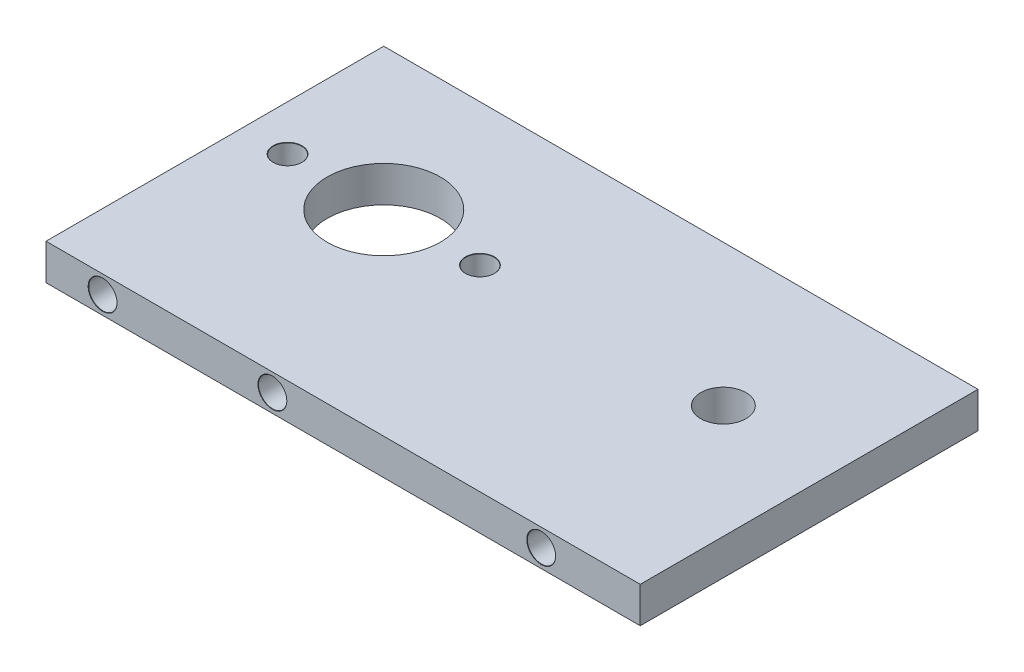
SolidWorks part; units mm, degrees
ref_plane "Front Plane" through (0, 0, 0) normal (0, 0, 1) x (1, 0, 0)
ref_plane "Top Plane" through (0, 0, 0) normal (0, 1, 0) x (1, 0, 0)
ref_plane "Right Plane" through (0, 0, 0) normal (1, 0, 0) x (0, 0, -1)
sketch "Sketch1" plane through (0, 0, 0) normal (0, 1, 0) x (1, 0, 0)
  line L0 (-12.5, -12.5) -> (-12.5, -17.34)
  line L1 (12.5, -12.5) -> (-12.5, -12.5) construction
  line L2 (12.5, -12.5) -> (12.5, 12.5)
  line L3 (12.5, 12.5) -> (-12.5, 12.5)
  line L4 (-12.5, -12.5) -> (-12.5, 12.5)
  line L5 (12.5, -12.5) -> (-12.5, 12.5) construction
  line L6 (12.5, 12.5) -> (-12.5, -12.5) construction
  line L7 (-12.5, -17.34) -> (12.5, -17.34)
  line L8 (12.5, -17.34) -> (12.5, -12.5)
  circle A0 centre (0, 0) radius 12.5 construction
  point P0 (0, 0)
  dimension "D1" = 25
  dimension "D2" = 17.34
extrude "Boss-Extrude1" add sketch "Sketch1" along normal blind 3.175
sketch "Sketch2" plane through (0, 3.175, 0) normal (0, 1, 0) x (1, 0, 0)
  line L0 (-8.5, 0) -> (8.5, 0) construction
  point P0 (-8.5, 0)
  point P1 (8.5, 0)
  point P2 (0, 0)
  dimension "D1" = 17
hole_wizard "Tap Drill for M3x0.5 Tap1" positions "Sketch2" profile "Sketch4" hole size "M3x0.5" standard "ANSI Metric" end condition through all
sketch "Sketch4" plane through (-8.5, 3.175, 0) normal (1, 0, 0) x (0, 0, 1)
  line L0 (0, 0) -> (0, 3.175)
  line L1 (0, 3.175) -> (1.25, 3.175)
  line L2 (1.25, 3.175) -> (1.25, 0.025)
  line L3 (1.25, 0.025) -> (1.275, 0)
  line L5 (1.275, 0) -> (0, 0)
  line L6 (-1.25, 0.025) -> (-1.275, 0) construction
  line L11 (0, -6.35) -> (0, 107.95) construction
  dimension "Thru Hole Dia." = 2.5
  dimension "Thru Hole Depth" = 3.175
  dimension "Near C'Sink Dia." = 2.55
  dimension "Near C'Sink Angle" = 90
sketch "Sketch8" plane through (0, 3.175, 0) normal (0, 1, 0) x (1, 0, 0)
  circle A0 centre (0, 0) radius 5
  dimension "D1" = 10
extrude "Cut-Extrude1" cut sketch "Sketch8" against normal up to next
sketch "Sketch9" plane through (0, 3.175, 0) normal (0, 1, 0) x (1, 0, 0)
  line L0 (0, 0) -> (30, 0) construction
  line L1 (12.5, 12.5) -> (40, 12.5)
  line L2 (40, 12.5) -> (40, -17.34)
  line L3 (40, -17.34) -> (12.5, -17.34)
  circle A0 centre (30, 0) radius 2
  dimension "D2" = 4
  dimension "D1" = 30
  dimension "D3" = 10
extrude "Boss-Extrude2" add sketch "Sketch9" against normal up to surface (3.175 mm away)
hole_wizard "Tap Drill for M3x0.5 Tap2" positions "Sketch7" profile "Sketch6" hole size "M3x0.5" standard "ANSI Metric"
sketch "Sketch7" plane through (0, 0, 17.34) normal (0, 0, 1) x (1, 0, 0)
  line L0 (-7.5, 1.5875) -> (7.5, 1.5875) construction
  line L2 (-12.5, 3.175) -> (40, 3.175) construction
  line L3 (-12.5, 0) -> (40, 0) construction
  line L4 (7.5, 1.5875) -> (40, 1.5875) construction
  line L5 (40, 0) -> (40, 3.175) construction
  point P0 (-7.5, 1.5875)
  point P2 (7.5, 1.5875)
  point P10 (0, 1.5875)
  point P24 (16.25, 1.5875)
  point P26 (31.25, 1.5875)
  point P29 (23.75, 1.5875)
  dimension "D1" = 15
  dimension "D2" = 7.5
  dimension "D3" = 7.5
sketch "Sketch6" plane through (-7.5, 1.5875, 17.34) normal (1, 0, 0) x (0, -1, 0)
  line L0 (0, 0) -> (0, 12.7511)
  line L1 (0, 12.7511) -> (1.25, 12)
  line L2 (1.25, 12) -> (1.25, 0.025)
  line L3 (1.25, 0.025) -> (1.275, 0)
  line L5 (1.275, 0) -> (0, 0)
  line L6 (-1.25, 0.025) -> (-1.275, 0) construction
  line L10 (0, 12.7511) -> (-1.25, 12) construction
  line L11 (0, -6.35) -> (0, 107.95) construction
  dimension "Hole Dia." = 2.5
  dimension "Hole Depth" = 12
  dimension "Near C'Sink Dia." = 2.55
  dimension "Near C'Sink Angle" = 90
  dimension "Drill Angle" = 118
